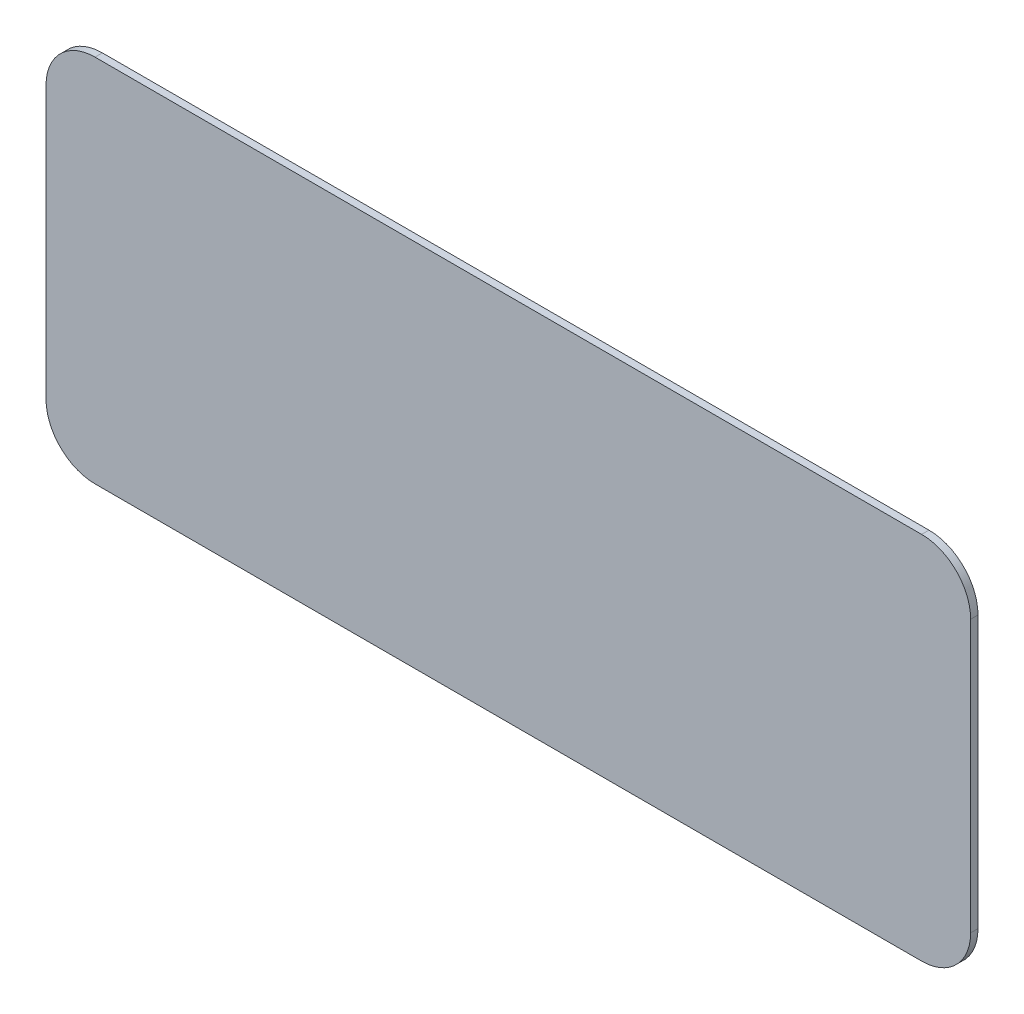
SolidWorks part; units mm, degrees
ref_plane "Alzado" through (0, 0, 0) normal (0, 0, 1) x (1, 0, 0)
ref_plane "Planta" through (0, 0, 0) normal (0, 1, 0) x (1, 0, 0)
ref_plane "Vista lateral" through (0, 0, 0) normal (1, 0, 0) x (0, 0, -1)
sketch "Croquis1" plane through (0, 0, 0) normal (0, 0, 1) x (1, 0, 0)
  line L0 (94.93, 0) -> (94.93, 110.871) construction
  line L1 (-262.531, -20) -> (74.93, -20) construction
  line L2 (-282.531, 110.871) -> (-282.531, 0) construction
  line L3 (74.93, 130.871) -> (-262.531, 130.871) construction
  line L4 (94.93, 0) -> (94.93, 110.871)
  line L5 (-262.531, -20) -> (74.93, -20)
  line L6 (-282.531, 110.871) -> (-282.531, 0)
  line L7 (74.93, 130.871) -> (-262.531, 130.871)
  arc A0 (94.93, 110.871) -> (74.93, 130.871) centre (74.93, 110.871) ccw construction
  arc A1 (74.93, -20) -> (94.93, 0) centre (74.93, 0) ccw construction
  arc A2 (-282.531, 0) -> (-262.531, -20) centre (-262.531, 0) ccw construction
  arc A3 (-262.531, 130.871) -> (-282.531, 110.871) centre (-262.531, 110.871) ccw construction
  arc A4 (94.93, 110.871) -> (74.93, 130.871) centre (74.93, 110.871) ccw
  arc A5 (74.93, -20) -> (94.93, 0) centre (74.93, 0) ccw
  arc A6 (-282.531, 0) -> (-262.531, -20) centre (-262.531, 0) ccw
  arc A7 (-262.531, 130.871) -> (-282.531, 110.871) centre (-262.531, 110.871) ccw
extrude "Saliente-Extruir1" add sketch "Croquis1" along normal blind 3
